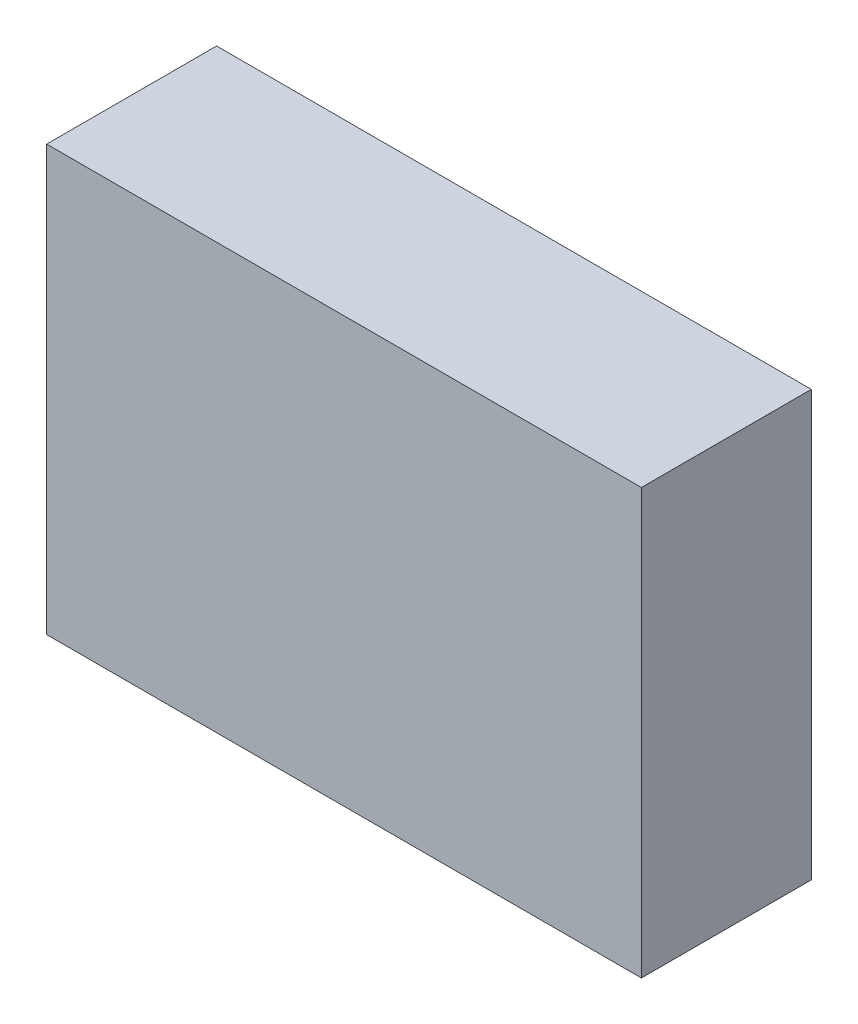
SolidWorks part; units mm, degrees
ref_plane "前视基准面" through (0, 0, 0) normal (0, 0, 1) x (1, 0, 0)
ref_plane "上视基准面" through (0, 0, 0) normal (0, 1, 0) x (1, 0, 0)
ref_plane "右视基准面" through (0, 0, 0) normal (1, 0, 0) x (0, 0, -1)
other "Configuration Table"
sketch "草图1" plane through (0, 0, 0) normal (0, 0, 1) x (1, 0, 0)
  line L1 (-35, -25) -> (35, -25)
  line L2 (-35, -25) -> (-35, 25)
  line L3 (-35, 25) -> (35, 25)
  line L4 (35, -25) -> (35, 25)
  line L5 (-35, -25) -> (35, 25) construction
  line L6 (-35, 25) -> (35, -25) construction
  point P0 (0, 0)
extrude "凸台-拉伸1" add sketch "草图1" along normal blind 20
